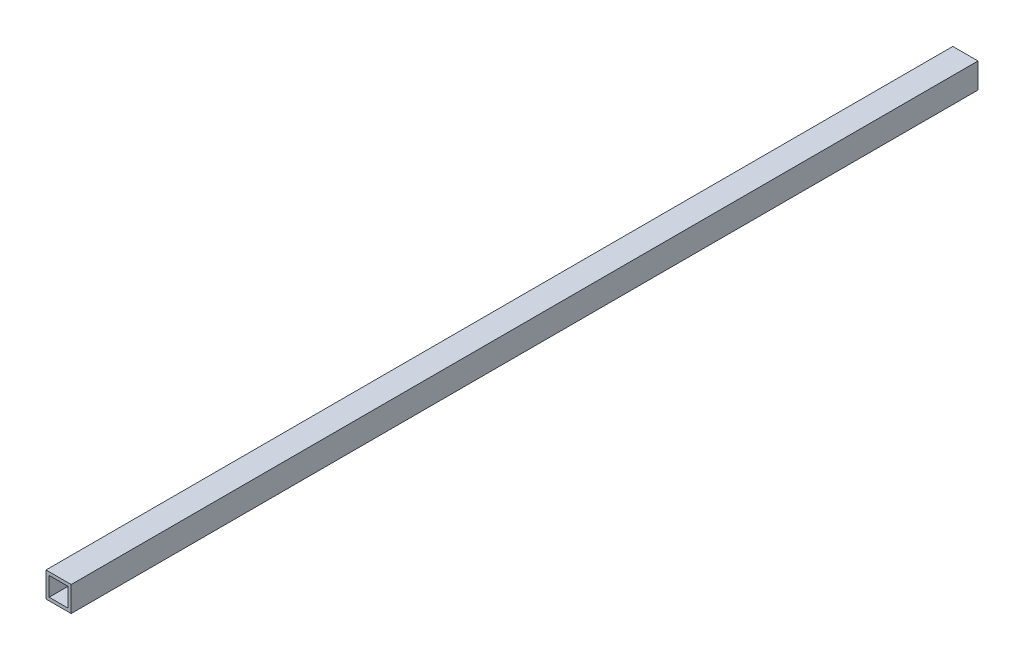
SolidWorks part; units mm, degrees
material "6061 Alloy"
ref_plane "Front Plane" through (0, 0, 0) normal (0, 0, 1) x (1, 0, 0)
ref_plane "Top Plane" through (0, 0, 0) normal (0, 1, 0) x (1, 0, 0)
ref_plane "Right Plane" through (0, 0, 0) normal (1, 0, 0) x (0, 0, -1)
sketch "Sketch1" plane through (0, 0, 0) normal (0, 0, 1) x (1, 0, 0)
  line L0 (12.7, 0) -> (9.525, 0) construction
  line L1 (-12.7, 0) -> (12.7, 0) construction
  line L2 (0, 12.7) -> (0, -12.7)
  point P7 (0, 0)
sketch "Sketch2" plane through (0, 0, 0) normal (1, 0, 0) x (0, 0, -1)
  line L0 (457.2, 0) -> (-457.2, 0)
  point P4 (0, 0)
  dimension "Length" = 914.4
sketch "Sketch3" plane through (0, 0, 0) normal (0, 0, 1) x (1, 0, 0)
  line L0 (-12.7, 0) -> (12.7, 0) construction
  line L5 (12.7, -12.7) -> (-12.7, -12.7)
  line L6 (12.7, -12.7) -> (12.7, 12.7)
  line L11 (12.7, 12.7) -> (-12.7, 12.7)
  line L12 (-12.7, -12.7) -> (-12.7, 12.7)
  line L14 (12.7, -12.7) -> (-12.7, 12.7) construction
  line L15 (12.7, 12.7) -> (-12.7, -12.7) construction
  line L16 (9.525, -9.525) -> (-9.525, -9.525)
  line L17 (9.525, -9.525) -> (9.525, 9.525)
  line L18 (9.525, 9.525) -> (-9.525, 9.525)
  line L19 (-9.525, -9.525) -> (-9.525, 9.525)
  line L20 (9.525, -9.525) -> (-9.525, 9.525) construction
  line L21 (9.525, 9.525) -> (-9.525, -9.525) construction
  point P0 (0, 0)
  point P5 (0, 0)
  point P13 (9.525, -12.7)
  dimension "D1" = 3.175
  dimension "D3" = 25.4
  dimension "D4" = 25.4
extrude "Boss-Extrude1" add sketch "Sketch3" along normal up to vertex (457.2 mm away) and the other way up to vertex (457.2 mm away) up to point (0, 0, 457.2) other way up to point (0, 0, -457.2)
sketch "Sketch5" plane through (0, 0, 0) normal (1, 0, 0) x (0, 0, -1)
  line L0 (-457.2, 0) -> (457.2, 0) construction
  line L3 (-457.2, -12.7) -> (-457.2, 12.7) construction
  line L4 (457.2, -12.7) -> (457.2, 12.7) construction
  point P6 (-428.625, 0)
  point P7 (-419.1, 0)
  point P8 (419.1, 0)
  point P10 (428.625, 0)
  dimension "D1" = 28.575
  dimension "D2" = 38.1
  dimension "D3" = 28.575
  dimension "D4" = 38.1
equation "\"D1@Sketch3\"=\"Wall thickness@Sketch1\""
equation "\"D1@Sketch5\"=\"Width@Sketch1\"*1.125"
equation "\"D2@Sketch5\"=\"Width@Sketch1\"*1.5"
equation "\"D3@Sketch5\"=\"D1@Sketch5\""
equation "\"D4@Sketch5\"=\"D2@Sketch5\""
equation "\"D2@Sketch3\"=\"Wall Thickness@Sketch1\""
